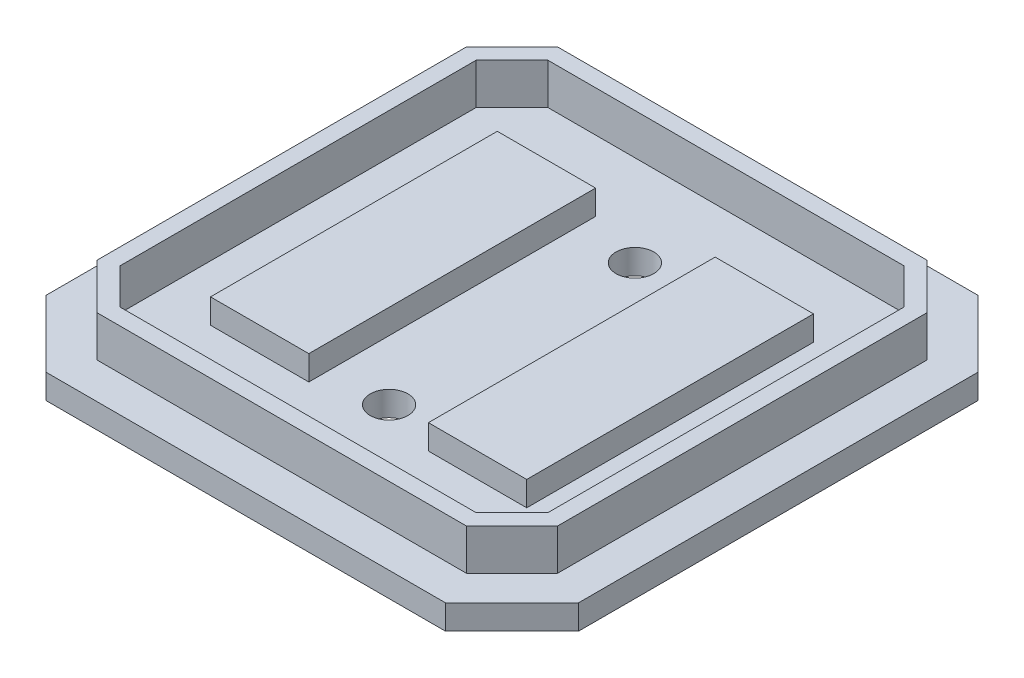
SolidWorks part; units mm, degrees
ref_plane "Ebene vorne" through (0, 0, 0) normal (0, 0, 1) x (1, 0, 0)
ref_plane "Ebene oben" through (0, 0, 0) normal (0, 1, 0) x (1, 0, 0)
ref_plane "Ebene rechts" through (0, 0, 0) normal (1, 0, 0) x (0, 0, -1)
sketch "Sketch1" plane through (0, 0, 0) normal (0, 1, 0) x (1, 0, 0)
  line L1 (-32.5, -32.5) -> (32.5, -32.5)
  line L2 (-32.5, -32.5) -> (-32.5, 32.5)
  line L3 (-32.5, 32.5) -> (32.5, 32.5)
  line L4 (32.5, -32.5) -> (32.5, 32.5)
  line L5 (-32.5, -32.5) -> (32.5, 32.5) construction
  line L6 (-32.5, 32.5) -> (32.5, -32.5) construction
  point P0 (0, 0)
  dimension "D1" = 65
  dimension "D2" = 65
extrude "Extrude1" add sketch "Sketch1" along normal blind 3
chamfer "Chamfer1" distance 8.125 angle 45 4 edges at (-32.5, 1.5, 32.5) (-32.5, 1.5, -32.5) (32.5, 1.5, -32.5) (32.5, 1.5, 32.5)
sketch "Sketch2" plane through (0, 3, 0) normal (0, 1, 0) x (1, 0, 0)
  line L0 (-28.1, 22.5525) -> (-28.1, -22.5525)
  line L1 (-28.1, -22.5525) -> (-22.5525, -28.1)
  line L2 (-22.5525, -28.1) -> (22.5525, -28.1)
  line L3 (22.5525, -28.1) -> (28.1, -22.5525)
  line L4 (28.1, -22.5525) -> (28.1, 22.5525)
  line L5 (28.1, 22.5525) -> (22.5525, 28.1)
  line L6 (22.5525, 28.1) -> (-22.5525, 28.1)
  line L7 (-22.5525, 28.1) -> (-28.1, 22.5525)
  line L8 (24.375, 32.5) -> (-24.375, 32.5) construction
  line L11 (-32.5, 24.375) -> (-32.5, -24.375) construction
  line L12 (-24.375, -32.5) -> (24.375, -32.5) construction
  line L13 (32.5, -24.375) -> (32.5, 24.375) construction
  line L19 (-32.5, -24.375) -> (-24.375, -32.5) construction
  line L20 (24.375, -32.5) -> (32.5, -24.375) construction
  line L22 (-24.375, 32.5) -> (-32.5, 24.375) construction
  line L23 (32.5, 24.375) -> (24.375, 32.5) construction
  line L24 (-26.1, 21.724) -> (-26.1, -11.2726)
  line L25 (-26.1, -11.2726) -> (-26.1, -21.724)
  line L26 (-26.1, -21.724) -> (-21.724, -26.1)
  line L27 (-21.724, -26.1) -> (21.724, -26.1)
  line L28 (21.724, -26.1) -> (26.1, -21.724)
  line L29 (26.1, -21.724) -> (26.1, 21.724)
  line L30 (26.1, 21.724) -> (21.724, 26.1)
  line L31 (21.724, 26.1) -> (-21.724, 26.1)
  line L32 (-21.724, 26.1) -> (-26.1, 21.724)
  dimension "D1" = 4.4
  dimension "D2" = 4.4
  dimension "D3" = 4.4
  dimension "D4" = 4.4
  dimension "D5" = 4.4
  dimension "D6" = 4.4
  dimension "D7" = 4.4
  dimension "D8" = 4.4
  dimension "D9" = 2
  dimension "D10" = 2
  dimension "D11" = 2
  dimension "D12" = 2
  dimension "D13" = 2
  dimension "D14" = 2
  dimension "D15" = 2
  dimension "D16" = 2
extrude "Extrude2" add sketch "Sketch2" along normal blind 5 contours L6 L7 L0 L1 L2 L3 L4 L5 L32 L31 L30 L29 L28 L27 L26 L25 L24
sketch "Sketch3" plane through (0, 3, 0) normal (0, 1, 0) x (1, 0, 0)
  line L3 (-19.2967, 17.5) -> (-7.2967, 17.5)
  line L4 (-19.2967, 17.5) -> (-19.2967, -17.5)
  line L5 (-19.2967, -17.5) -> (-7.2967, -17.5)
  line L6 (-7.2967, 17.5) -> (-7.2967, -17.5)
  dimension "D1" = 35
  dimension "D2" = 12
  dimension "D3" = 17.5
extrude "Extrude3" add sketch "Sketch3" along normal blind 3
mirror "Mirror1" about plane through (0, 0, 0) normal (1, 0, 0) of "Extrude3"
sketch "Sketch4" plane through (0, 3, 0) normal (0, 1, 0) x (1, 0, 0)
  line L0 (0, -4.4) -> (0, 4.4) construction
  circle A0 centre (0, 15) radius 2.3
  circle A1 centre (0, -15) radius 2.3
  dimension "D1" = 4.6
  dimension "D2" = 4.6
  dimension "D3" = 30
  dimension "D4" = 15
extrude "Extrude4" cut sketch "Sketch4" against normal blind 3
